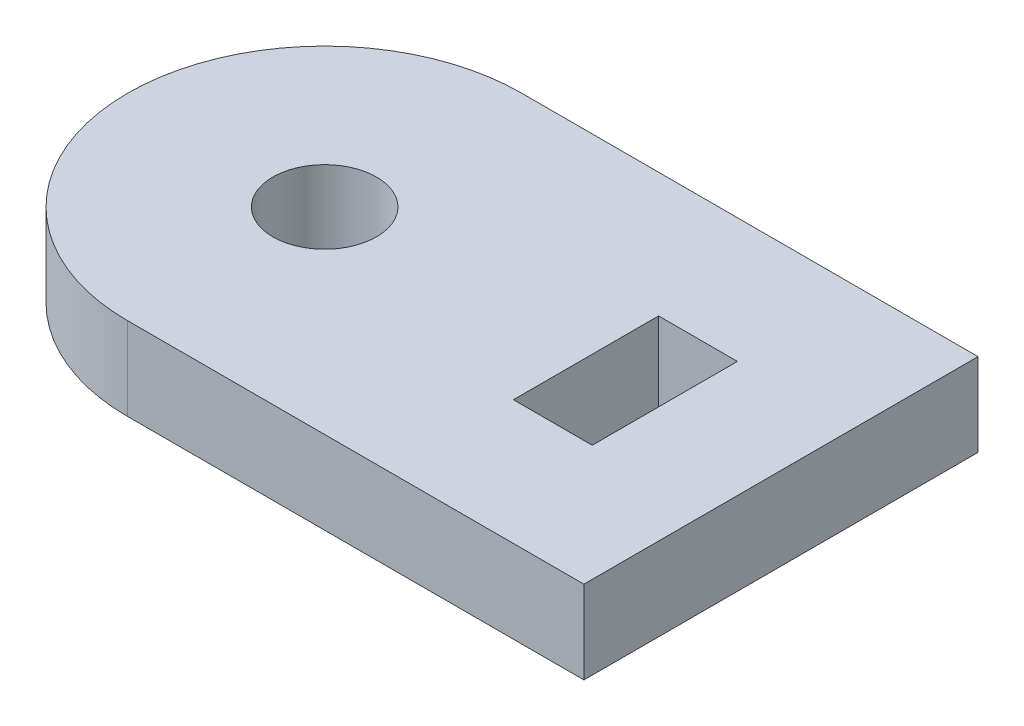
SolidWorks part; units mm, degrees
ref_plane "Front Plane" through (0, 0, 0) normal (0, 0, 1) x (1, 0, 0)
ref_plane "Top Plane" through (0, 0, 0) normal (0, 1, 0) x (1, 0, 0)
ref_plane "Right Plane" through (0, 0, 0) normal (1, 0, 0) x (0, 0, -1)
sketch "Sketch1" plane through (0, 0, 0) normal (0, 1, 0) x (1, 0, 0)
  line L0 (0, 0) -> (22, 0)
  line L1 (22, 0) -> (22, 19)
  line L2 (22, 19) -> (0, 19)
  line L3 (22, 9.5) -> (14.5, 9.5) construction
  line L4 (0, 19) -> (0, 0) construction
  line L6 (16.4, 13) -> (12.6, 13)
  line L7 (16.4, 13) -> (16.4, 6)
  line L8 (16.4, 6) -> (12.6, 6)
  line L9 (12.6, 13) -> (12.6, 6)
  line L10 (16.4, 13) -> (12.6, 6) construction
  line L11 (16.4, 6) -> (12.6, 13) construction
  arc A0 (0, 0) -> (0, 19) centre (0, 9.5) cw
  circle A1 centre (0, 9.5) radius 2.5
  dimension "D1" = 5
  dimension "D4" = 9.5
  dimension "D2" = 19
  dimension "D3" = 22
  dimension "D5" = 7.5
  dimension "D6" = 3.8
  dimension "D7" = 7
extrude "Boss-Extrude1" add sketch "Sketch1" along normal blind 4 contours L2 L4 A1 L0 L1 | L4 A0 A1
